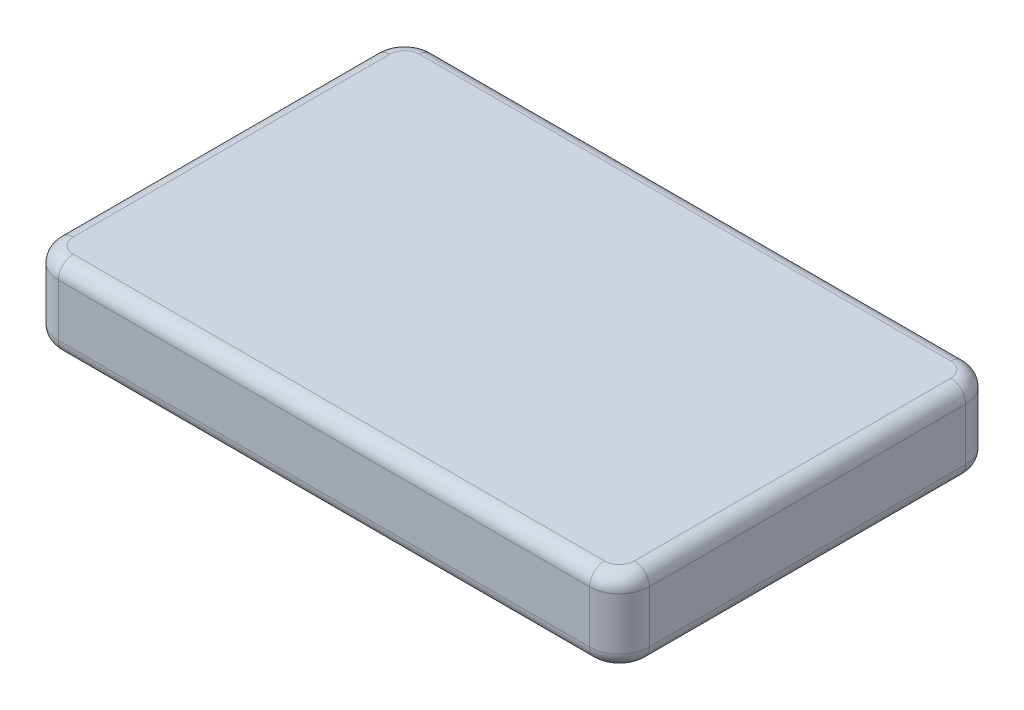
SolidWorks part; units mm, degrees
ref_plane "Alzado" through (0, 0, 0) normal (0, 0, 1) x (1, 0, 0)
ref_plane "Planta" through (0, 0, 0) normal (0, 1, 0) x (1, 0, 0)
ref_plane "Vista lateral" through (0, 0, 0) normal (1, 0, 0) x (0, 0, -1)
sketch "Croquis1" plane through (0, 0, 0) normal (0, 1, 0) x (1, 0, 0)
  line L1 (19.8, -12.6) -> (-19.8, -12.6)
  line L2 (19.8, -12.6) -> (19.8, 12.6)
  line L3 (19.8, 12.6) -> (-19.8, 12.6)
  line L4 (-19.8, -12.6) -> (-19.8, 12.6)
  line L5 (19.8, -12.6) -> (-19.8, 12.6) construction
  line L6 (19.8, 12.6) -> (-19.8, -12.6) construction
  point P0 (0, 0)
  dimension "D1" = 39.6
  dimension "D2" = 25.2
extrude "Saliente-Extruir1" add sketch "Croquis1" along normal blind 5.5
fillet "Redondeo1" radius 2 1 edges at (-19.8, 2.75, 12.6)
fillet "Redondeo2" radius 2 1 edges at (19.8, 2.75, 12.6)
fillet "Redondeo3" radius 2 1 edges at (19.8, 2.75, -12.6)
fillet "Redondeo4" radius 2 1 edges at (-19.8, 2.75, -12.6)
fillet "Redondeo5" radius 1 16 edges at (0, 0, 12.6) (19.2142, 0, 12.0142) (19.8, 0, 0) (-19.8, 0, 0) (0, 0, -12.6) (-19.8, 5.5, 0) (0, 5.5, 12.6) (19.8, 5.5, 0) (0, 5.5, -12.6) (-19.2142, 0, 12.0142) (-19.2142, 5.5, 12.0142) (19.2142, 5.5, 12.0142) (19.2142, 0, -12.0142) (19.2142, 5.5, -12.0142) (-19.2142, 0, -12.0142) (-19.2142, 5.5, -12.0142)
